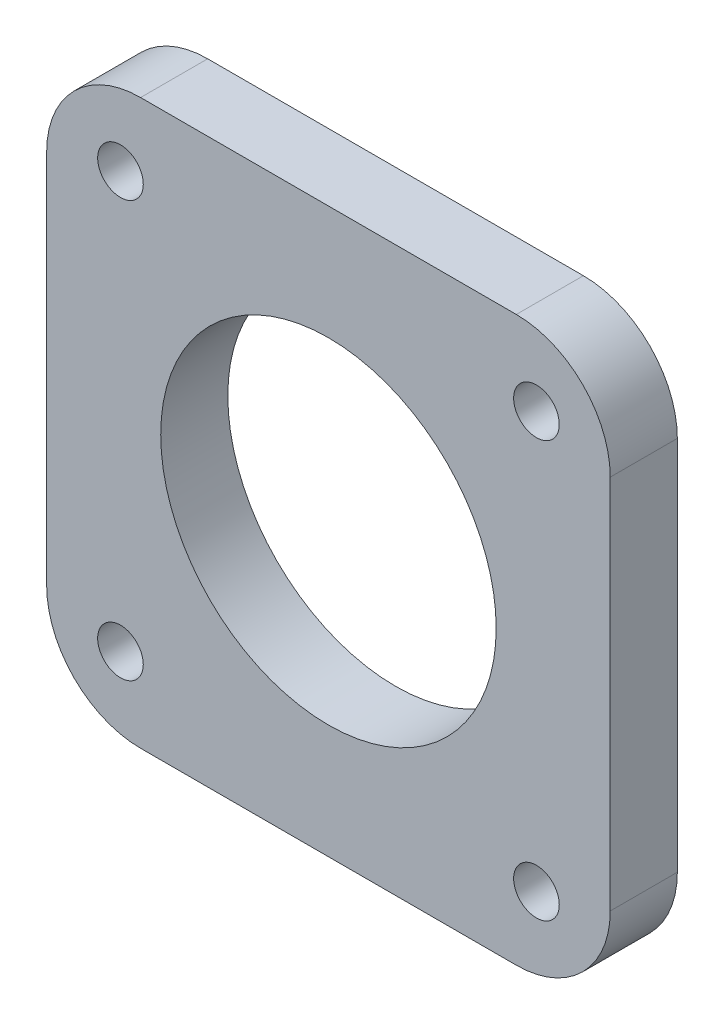
SolidWorks part; units mm, degrees
ref_plane "前视基准面" through (0, 0, 0) normal (0, 0, 1) x (1, 0, 0)
ref_plane "上视基准面" through (0, 0, 0) normal (0, 1, 0) x (1, 0, 0)
ref_plane "右视基准面" through (0, 0, 0) normal (1, 0, 0) x (0, 0, -1)
other "Configuration Table"
sketch "草图1" plane through (0, 0, 0) normal (0, 0, 1) x (1, 0, 0)
  line L5 (-21, -21) -> (21, -21)
  line L6 (-21, -21) -> (-21, 21)
  line L7 (-21, 21) -> (21, 21)
  line L8 (21, -21) -> (21, 21)
  line L9 (-21, -21) -> (21, 21) construction
  line L10 (-21, 21) -> (21, -21) construction
  circle A0 centre (0, 0) radius 12.5
  circle A1 centre (-15.5, -15.5) radius 1.7
  circle A2 centre (15.5, -15.5) radius 1.7
  circle A3 centre (15.5, 15.5) radius 1.7
  circle A4 centre (-15.5, 15.5) radius 1.7
  point P0 (0, 0)
  point P16 (15.5, -15.5)
  point P17 (-15.5, -15.5)
  point P18 (-15.5, 15.5)
  point P21 (15.5, 15.5)
  dimension "D1" = 25
  dimension "D2" = 3.4
  dimension "D3" = 3.4
  dimension "D4" = 3.4
  dimension "D5" = 3.4
  dimension "D6" = 42
  dimension "D7" = 42
extrude "凸台-拉伸1" add sketch "草图1" along normal blind 5
fillet "圆角1" radius 7 4 edges at (-21, 21, 2.5) (21, 21, 2.5) (21, -21, 2.5) (-21, -21, 2.5)
